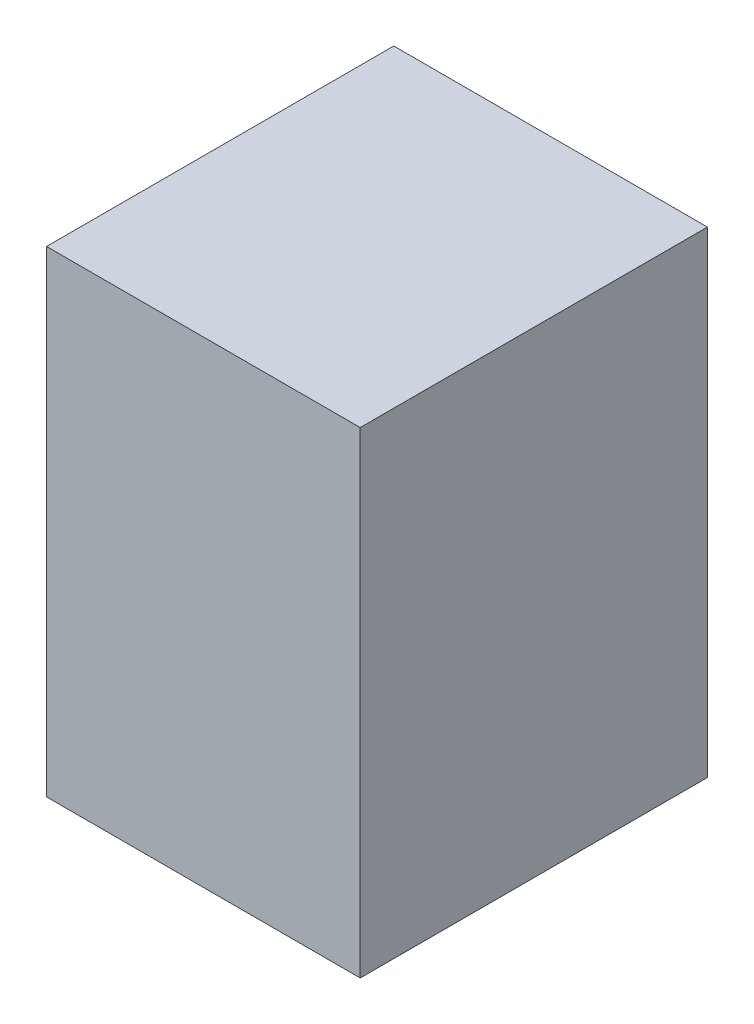
SolidWorks part; units mm, degrees
ref_plane "Front Plane" through (0, 0, 0) normal (0, 0, 1) x (1, 0, 0)
ref_plane "Top Plane" through (0, 0, 0) normal (0, 1, 0) x (1, 0, 0)
ref_plane "Right Plane" through (0, 0, 0) normal (1, 0, 0) x (0, 0, -1)
sketch "Sketch2" plane through (0, 0, 0) normal (0, 0, 1) x (1, 0, 0)
  line L1 (-20.1, 30.55) -> (20.1, 30.55)
  line L2 (-20.1, 30.55) -> (-20.1, -30.55)
  line L3 (-20.1, -30.55) -> (20.1, -30.55)
  line L4 (20.1, 30.55) -> (20.1, -30.55)
  line L5 (-20.1, 30.55) -> (20.1, -30.55) construction
  line L6 (-20.1, -30.55) -> (20.1, 30.55) construction
  point P0 (0, 0)
  dimension "D1" = 40.2
  dimension "D2" = 61.1
extrude "Boss-Extrude1" add sketch "Sketch2" along normal blind 44.5
ref_plane "Plane5" through (0, 0, 0) normal (0, 0, -1) x (-1, 0, 0)
